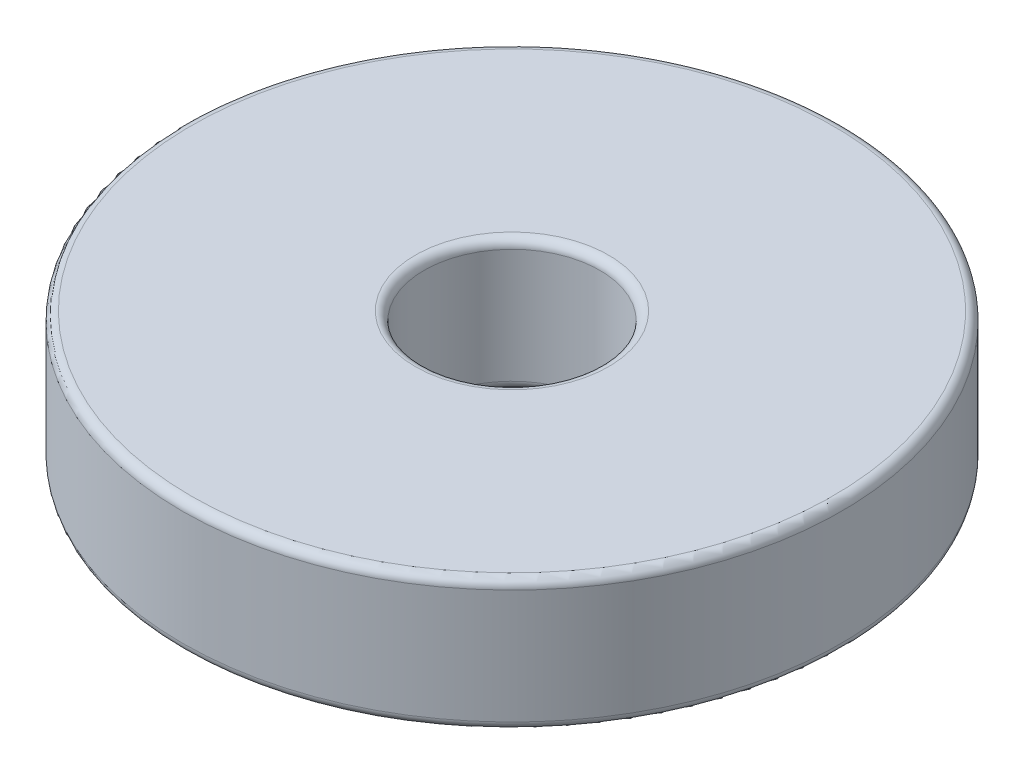
SolidWorks part; units mm, degrees
ref_plane "Front Plane" through (0, 0, 0) normal (0, 0, 1) x (1, 0, 0)
ref_plane "Top Plane" through (0, 0, 0) normal (0, 1, 0) x (1, 0, 0)
ref_plane "Right Plane" through (0, 0, 0) normal (1, 0, 0) x (0, 0, -1)
sketch "Sketch1" plane through (0, 0, 0) normal (0, 1, 0) x (1, 0, 0)
  circle A0 centre (0, 0) radius 2
  circle A1 centre (0, 0) radius 7.5
  dimension "D1" = 15
  dimension "D2" = 4
extrude "Boss-Extrude1" add sketch "Sketch1" along normal blind 3
fillet "Fillet1" radius 0.2 4 edges at (0, 0, 2) (0, 0, 7.5) (0, 3, 2) (0, 3, 7.5)
